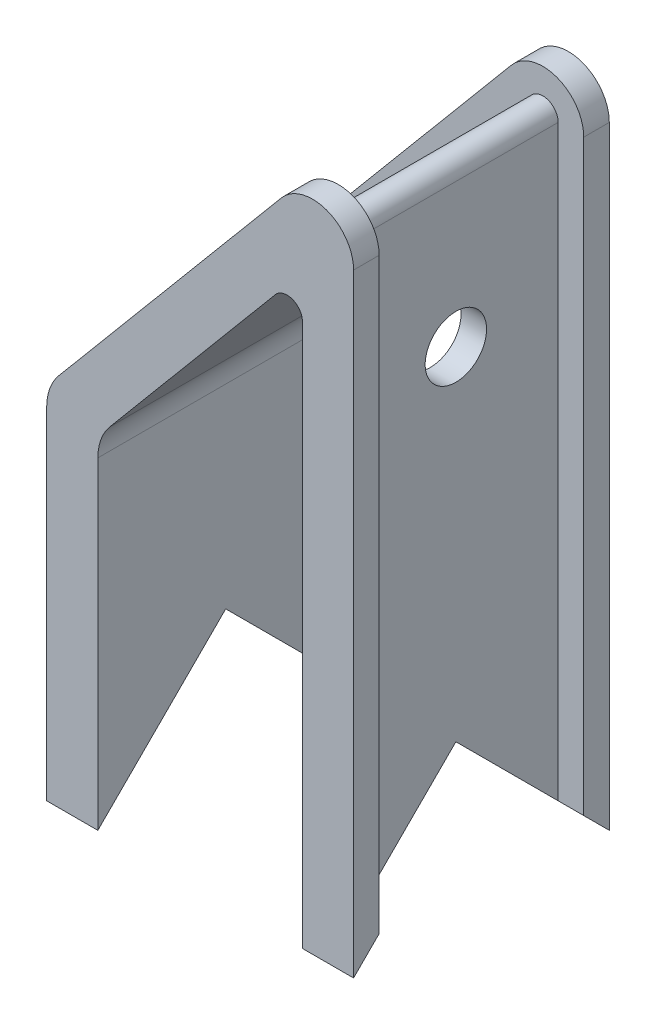
SolidWorks part; units mm, degrees
material "Alloy Steel"
ref_plane "Front Plane" through (0, 0, 0) normal (0, 0, 1) x (1, 0, 0)
ref_plane "Top Plane" through (0, 0, 0) normal (0, 1, 0) x (1, 0, 0)
ref_plane "Right Plane" through (0, 0, 0) normal (1, 0, 0) x (0, 0, -1)
sketch "Sketch1" plane through (0, 0, 0) normal (0, 0, 1) x (1, 0, 0)
  line L0 (0, -20.7161) -> (0, 122.2839) construction
  line L1 (0, 122.2839) -> (-50, 62.6962) construction
  line L2 (-50, 62.6962) -> (-50, -20.7161) construction
  line L3 (5, -20.7161) -> (5, 136.0213)
  line L4 (5, 136.0213) -> (-55, 64.5161)
  line L5 (-55, 64.5161) -> (-55, -20.7161)
  line L6 (-5, -20.7161) -> (-5, 108.5465)
  line L7 (-5, 108.5465) -> (-45, 60.8764)
  line L8 (-45, 60.8764) -> (-45, -20.7161)
  line L9 (5, -20.7161) -> (-5, -20.7161)
  line L10 (-55, -20.7161) -> (-45, -20.7161)
  dimension "D1" = 50
  dimension "D2" = 143
  dimension "D3" = 140
  dimension "D4" = 5
  dimension "D5" = 5
extrude "Boss-Extrude2" add sketch "Sketch1" along normal blind 50
sketch "Sketch2" plane through (0, -20.7161, 0) normal (0, -1, 0) x (1, 0, 0)
  line L0 (-55, 45) -> (-50, 45)
  line L1 (-55, 50) -> (-55, 0) construction
  line L2 (-50, 45) -> (-50, 5)
  line L3 (-50, 5) -> (-55, 5)
  line L4 (-55, 5) -> (-55, 45)
  line L5 (-55, 50) -> (-45, 50) construction
  line L6 (-55, 0) -> (-45, 0) construction
  dimension "D1" = 5
  dimension "D2" = 5
  dimension "D3" = 5
extrude "Cut-Extrude1" cut sketch "Sketch2" against normal up to body
ref_plane "Plane1" through (14.0433, 16.7361, 0) normal (0.6428, 0.766, 0) x (0, 0, -1)
sketch "Sketch3" plane through (14.0433, 16.7361, 0) normal (0.6428, 0.766, 0) x (0, 0, -1)
  line L0 (-45, 83.6026) -> (-45, 78.6026)
  line L1 (-50, 83.6026) -> (0, 83.6026) construction
  line L2 (-45, 78.6026) -> (-5, 78.6026)
  line L3 (-5, 78.6026) -> (-5, 83.6026)
  line L4 (-5, 83.6026) -> (-45, 83.6026)
  line L5 (-50, -17.1463) -> (-50, 83.6026) construction
  line L6 (0, -17.1463) -> (0, 83.6026) construction
  dimension "D1" = 5
  dimension "D2" = 5
  dimension "D3" = 5
extrude "Cut-Extrude4" cut sketch "Sketch3" against normal blind 25
sketch "Sketch5" plane through (14.0433, 16.7361, 0) normal (0.6428, 0.766, 0) x (0, 0, -1)
  line L0 (-45, 83.6026) -> (-45, 78.6026)
  line L1 (-50, 83.6026) -> (0, 83.6026) construction
  line L2 (-45, 78.6026) -> (-5, 78.6026)
  line L3 (-5, 78.6026) -> (-5, 83.6026)
  line L4 (-5, 83.6026) -> (-45, 83.6026)
  line L5 (-50, -17.1463) -> (-50, 83.6026) construction
  line L6 (0, -17.1463) -> (0, 83.6026) construction
  dimension "D1" = 5
  dimension "D2" = 5
  dimension "D3" = 5
extrude "Cut-Extrude5" cut sketch "Sketch5" along normal up to vertex
sketch "Sketch6" plane through (0, -20.7161, 0) normal (0, -1, 0) x (1, 0, 0)
  line L0 (5, 45) -> (0, 45)
  line L1 (5, 50) -> (5, 0) construction
  line L2 (0, 45) -> (0, 5)
  line L3 (0, 5) -> (5, 5)
  line L4 (-5, 50) -> (5, 50) construction
  line L5 (-5, 0) -> (5, 0) construction
  line L6 (5, 45) -> (5, 5)
  dimension "D1" = 5
  dimension "D2" = 5
extrude "Cut-Extrude6" cut sketch "Sketch6" against normal up to vertex
fillet "Fillet1" radius 10 4 edges at (-55, 64.5161, 2.5) (-55, 64.5161, 47.5) (-50, 62.6962, 25) (-45, 60.8764, 25)
fillet "Fillet2" radius 3 2 edges at (0, 122.2839, 25) (-5, 108.5465, 25)
fillet "Fillet3" radius 8 2 edges at (5, 136.0213, 2.5) (5, 136.0213, 47.5)
sketch "Sketch8" plane through (-55, 0, 0) normal (-1, 0, 0) x (0, 0, 1)
  line L0 (25, 59.0565) -> (25, -20.7161) construction
  line L1 (45, 59.0565) -> (5, 59.0565) construction
  line L2 (5, -20.7161) -> (45, -20.7161) construction
  line L3 (0, -20.7161) -> (25, 19.1702)
  line L4 (25, 19.1702) -> (50, -20.7161)
  line L5 (50, -20.7161) -> (0, -20.7161)
extrude "Cut-Extrude7" cut sketch "Sketch8" against normal up to surface (60 mm away) up to face at (5, 46.6627, 2.5)
sketch "Sketch9" plane through (5, 0, 0) normal (1, 0, 0) x (0, 0, -1)
  line L0 (0, -5.8298) -> (-25, 19.1702)
  line L1 (0, -20.7161) -> (0, 114.0415) construction
  line L2 (49.2462, -55.076) -> (-25, 19.1702) construction
  line L3 (-25, 19.1702) -> (-50, -5.8298)
  line L4 (-50, -20.7161) -> (-50, 114.0415) construction
  line L5 (-25, 19.1702) -> (-99.2462, -55.076) construction
  line L6 (-50, -5.8298) -> (0, -5.8298)
extrude "Cut-Extrude8" cut sketch "Sketch9" against normal through all
sketch "Sketch10" plane through (-55, 0, 0) normal (-1, 0, 0) x (0, 0, 1)
  line L0 (0, -5.8298) -> (50, -5.8298)
  line L1 (50, -5.8298) -> (50, -20.7161)
  line L2 (50, -5.8298) -> (50, -20.7161) construction
  line L3 (50, -20.7161) -> (0, -20.7161)
  line L4 (0, -20.7161) -> (0, -5.8298)
extrude "Cut-Extrude9" cut sketch "Sketch10" against normal through all
sketch "Sketch11" plane through (-60.2131, 50.5248, 0) normal (-0.766, 0.6428, 0) x (0, 0, 1)
  line L0 (25, 85.4325) -> (25, 19.5284) construction
  line L1 (45, 85.4325) -> (5, 85.4325) construction
  line L2 (5, 19.5284) -> (45, 19.5284) construction
  circle A0 centre (25, 55.4325) radius 6
  dimension "D1" = 12
  dimension "D2" = 30
extrude "Cut-Extrude10" cut sketch "Sketch11" against normal up to next
sketch "Sketch12" plane through (0, 0, 0) normal (1, 0, 0) x (0, 0, -1)
  line L0 (-25, 114.0415) -> (-25, 19.1702) construction
  line L1 (-5, 114.0415) -> (-45, 114.0415) construction
  circle A0 centre (-25, 86.0415) radius 6
  dimension "D1" = 12
  dimension "D2" = 28
extrude "Cut-Extrude11" cut sketch "Sketch12" against normal up to next
